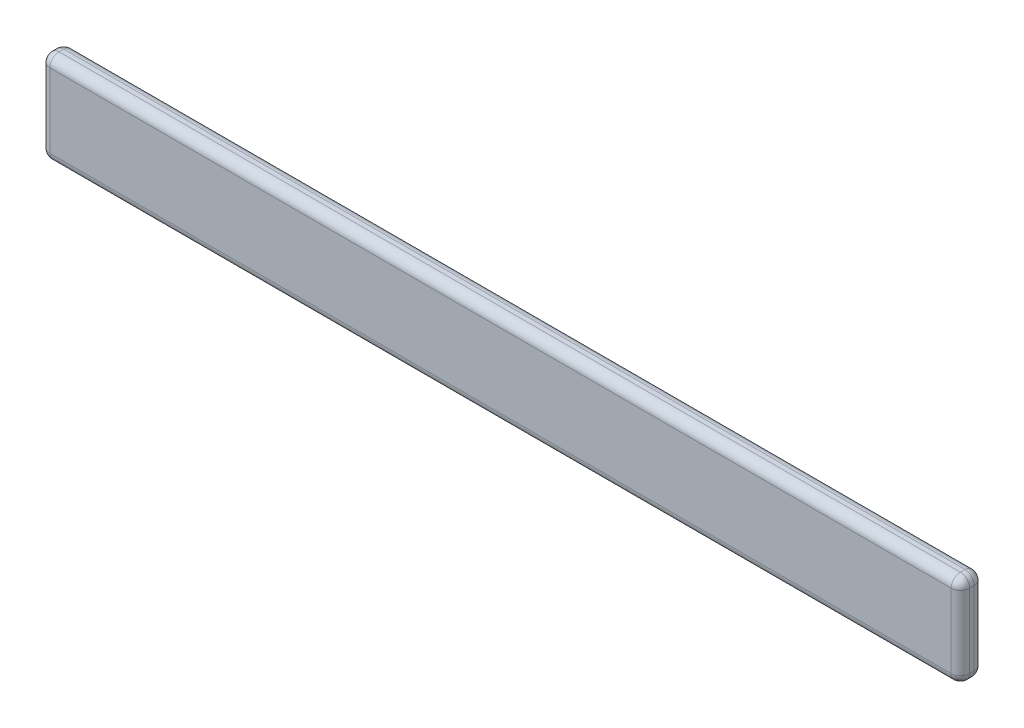
SolidWorks part; units mm, degrees
ref_plane "Front Plane" through (0, 0, 0) normal (0, 0, 1) x (1, 0, 0)
ref_plane "Top Plane" through (0, 0, 0) normal (0, 1, 0) x (1, 0, 0)
ref_plane "Right Plane" through (0, 0, 0) normal (1, 0, 0) x (0, 0, -1)
sketch "Sketch2" plane through (0, 0, 0) normal (1, 0, 0) x (0, 0, -1)
  line L1 (25, -100) -> (-25, -100)
  line L2 (25, -100) -> (25, 100)
  line L3 (25, 100) -> (-25, 100)
  line L4 (-25, -100) -> (-25, 100)
  line L5 (25, -100) -> (-25, 100) construction
  line L6 (25, 100) -> (-25, -100) construction
  point P0 (0, 0)
  dimension "D1" = 200
  dimension "D2" = 50
extrude "Boss-Extrude1" add sketch "Sketch2" along normal blind 1990
fillet "Fillet1" radius 20 12 edges at (0, -100, 0) (1990, -100, 0) (1990, 100, 0) (0, 100, 0) (995, -100, -25) (1990, 0, -25) (995, 100, -25) (0, 0, -25) (995, 100, 25) (1990, 0, 25) (995, -100, 25) (0, 0, 25)
